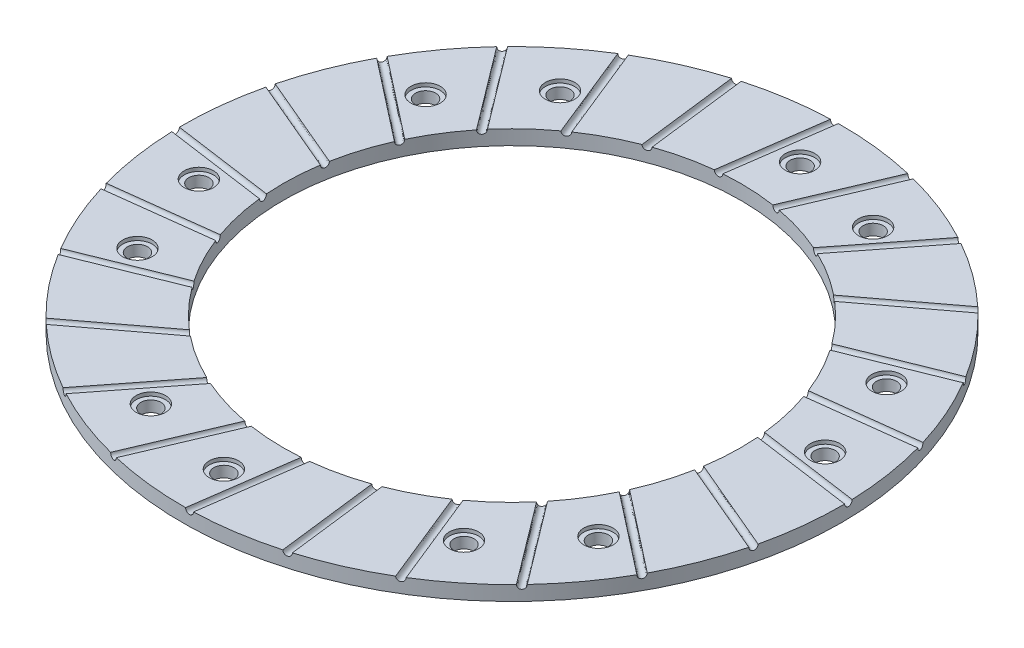
SolidWorks part; units mm, degrees
ref_plane "Front" through (0, 0, 0) normal (0, 0, 1) x (1, 0, 0)
ref_plane "Top" through (0, 0, 0) normal (0, 1, 0) x (1, 0, 0)
ref_plane "Right" through (0, 0, 0) normal (1, 0, 0) x (0, 0, -1)
sketch "Sketch1" plane through (0, 0, 0) normal (0, 1, 0) x (1, 0, 0)
  circle A0 centre (0, 0) radius 62.5
  circle A1 centre (0, 0) radius 75.75 construction
  dimension "D1" = 125
  dimension "D2" = 151.5
extrude "Extrude-Thin1" add sketch "Sketch1" along normal blind 4 thin
sketch "Sketch2" plane through (0, 4, 0) normal (0, 1, 0) x (1, 0, 0)
  line L0 (0, 0) -> (-15.65, 0) construction
  line L1 (-15.65, 0) -> (21.4517, 87.4061) construction
  circle A0 centre (0, 0) radius 90 construction
  dimension "D1" = 67
  dimension "D2" = 15.65
sketch "Sketch3" plane through (0, 0, 0) normal (0, 0, 1) x (1, 0, 0)
  circle A0 centre (-15.65, 4) radius 1.125
  dimension "D1" = 2.25
extrude "Cut-Extrude1" cut sketch "Sketch3" along direction (0.3907, 0, -0.9205) on the side against the normal through all
pattern_circular "CirPattern1" count 24 over 360 about axis through (0, 4, 0) along (0, -1, 0) of "Cut-Extrude1"
hole_wizard "CBORE for M5 Hex Head Bolt1" positions "Sketch4" profile "Sketch5" counterbore size "M5" standard "ISO" end condition through all
sketch "Sketch4" plane through (0, 4, 0) normal (0, 1, 0) x (1, 0, 0)
  circle A0 centre (0, 0) radius 75.75 construction
  point P0 (3, 75.6906)
  point P4 (28.4174, 70.2176)
  dimension "D1" = 3
  dimension "D2" = 26
sketch "Sketch5" plane through (3, 4, -75.6906) normal (1, 0, 0) x (0, 0, 1)
  line L0 (0, 0) -> (0, 4)
  line L1 (0, 4) -> (2.75, 4)
  line L3 (2.75, 4) -> (2.75, 1)
  line L4 (2.75, 1) -> (4, 1)
  line L5 (4, 1) -> (4, 0)
  line L7 (4, 0) -> (0, 0)
  line L11 (0, -6.35) -> (0, 107.95) construction
  dimension "Thru Hole Dia." = 5.5
  dimension "Thru Hole Depth" = 4
  dimension "C'Bore Dia." = 8
  dimension "C'Bore Depth" = 1
pattern_circular "CirPattern2" count 6 over 360 about axis through (0, 0, 0) along (0, 1, 0) of "CBORE for M5 Hex Head Bolt1"
